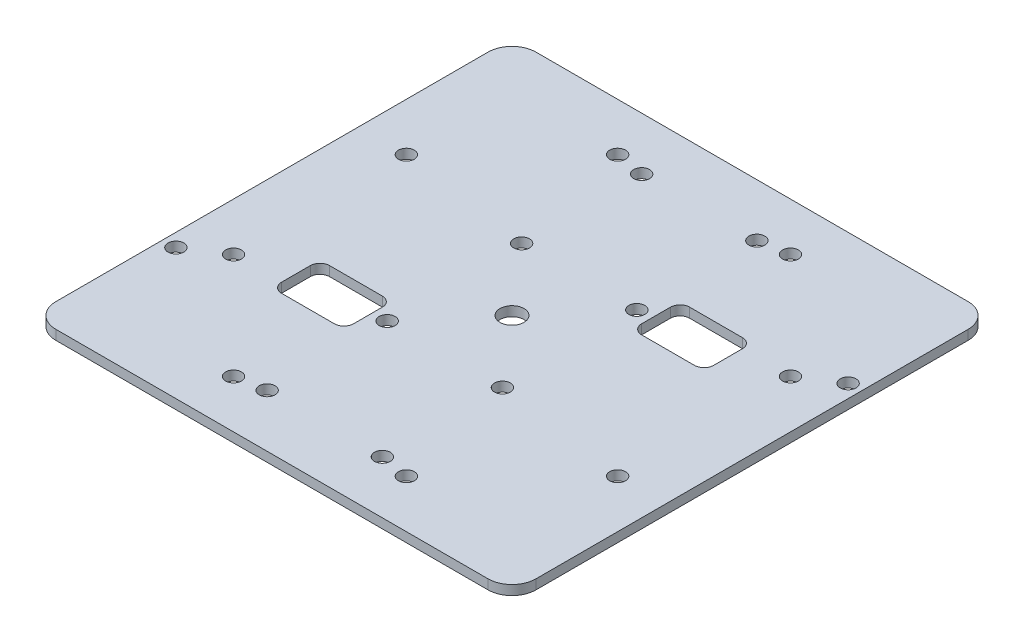
SolidWorks part; units mm, degrees
ref_plane "前视基准面" through (0, 0, 0) normal (0, 0, 1) x (1, 0, 0)
ref_plane "上视基准面" through (0, 0, 0) normal (0, 1, 0) x (1, 0, 0)
ref_plane "右视基准面" through (0, 0, 0) normal (1, 0, 0) x (0, 0, -1)
sketch "草图1" plane through (0, 0, 0) normal (0, 1, 0) x (1, 0, 0)
  line L1 (-50, -50) -> (50, -50)
  line L2 (-50, -50) -> (-50, 50)
  line L3 (-50, 50) -> (50, 50)
  line L4 (50, -50) -> (50, 50)
  line L5 (-50, -50) -> (50, 50) construction
  line L6 (-50, 50) -> (50, -50) construction
  point P0 (0, 0)
  dimension "D1" = 100
  dimension "D2" = 100
extrude "凸台-拉伸1" add sketch "草图1" along normal blind 2
sketch "草图2" plane through (0, 2, 0) normal (0, 1, 0) x (1, 0, 0)
  circle A0 centre (0, 0) radius 2.5
  dimension "D1" = 5
extrude "临时配合孔" cut sketch "草图2" against normal up to next
sketch "草图3" plane through (0, 2, 0) normal (0, 1, 0) x (1, 0, 0)
  line L1 (-12, 39) -> (12, 39) construction
  line L2 (-12, 39) -> (-12, -39) construction
  line L3 (-12, -39) -> (12, -39) construction
  line L4 (12, 39) -> (12, -39) construction
  line L5 (-12, 39) -> (12, -39) construction
  line L6 (-12, -39) -> (12, 39) construction
  circle A0 centre (-12, 39) radius 1.65
  circle A1 centre (12, 39) radius 1.65
  point P0 (0, 0)
  dimension "D3" = 3.3
  dimension "D1" = 24
  dimension "D2" = 78
extrude "切除-拉伸2" cut sketch "草图3" against normal up to next
pattern_linear "阵列(线性)1" count 2 spacing 25 along (0, 0, 1) of "切除-拉伸2"
mirror "镜向1" about plane through (0, 0, 0) normal (0, 0, 1) of "阵列(线性)1", "切除-拉伸2"
sketch "草图4" plane through (0, 0, 0) normal (1, 0, 0) x (0, 0, -1)
  line L0 (0, 0) -> (0, 2) construction
  line L1 (-50, 2) -> (50, 2) construction
sketch "草图5" plane through (0, 2, 0) normal (0, 1, 0) x (1, 0, 0)
  line L0 (50, 50) -> (-50, 50) construction
  line L1 (50, -50) -> (50, 50) construction
  circle A0 centre (47.25, 22.75) radius 1.65
  dimension "D2" = 3.3
  dimension "D1" = 27.25
  dimension "D3" = 2.75
extrude "切除-拉伸3" cut sketch "草图5" against normal up to next
pattern_circular "阵列(圆周)1" count 2 over 360 about axis through (0, 0, 0) along (0, 1, 0) of "切除-拉伸3"
sketch "草图6" plane through (0, 2, 0) normal (0, 1, 0) x (1, 0, 0)
  line L1 (-40, -18) -> (40, -18) construction
  line L2 (-40, -18) -> (-40, 18) construction
  line L3 (-40, 18) -> (40, 18) construction
  line L4 (40, -18) -> (40, 18) construction
  line L5 (-40, -18) -> (40, 18) construction
  line L6 (-40, 18) -> (40, -18) construction
  circle A0 centre (-40, 18) radius 1.65
  circle A1 centre (-40, -18) radius 1.65
  circle A2 centre (40, -18) radius 1.65
  circle A3 centre (40, 18) radius 1.65
  point P0 (0, 0)
  dimension "D3" = 3.3
  dimension "D1" = 36
  dimension "D2" = 80
extrude "切除-拉伸4" cut sketch "草图6" against normal up to next
pattern_circular "阵列(圆周)2" count 2 over 90 about axis through (0, 0, 0) along (0, 1, 0) of "切除-拉伸4"
sketch "草图7" plane through (0, 2, 0) normal (0, 1, 0) x (1, 0, 0)
  line L1 (-15, -10) -> (15, -10) construction
  line L2 (-15, -10) -> (-15, 10) construction
  line L3 (-15, 10) -> (15, 10) construction
  line L4 (15, -10) -> (15, 10) construction
  line L5 (-15, -10) -> (15, 10) construction
  line L6 (-15, 10) -> (15, -10) construction
  line L7 (-15, -10) -> (-30, -10)
  line L8 (-15, -10) -> (-15, -20)
  line L9 (-15, -20) -> (-30, -20)
  line L10 (-30, -10) -> (-30, -20)
  line L11 (15, 10) -> (30, 10)
  line L12 (15, 10) -> (15, 20)
  line L13 (15, 20) -> (30, 20)
  line L14 (30, 10) -> (30, 20)
  point P0 (0, 0)
  dimension "D1" = 30
  dimension "D2" = 20
  dimension "D3" = 15
  dimension "D4" = 10
extrude "切除-拉伸5" cut sketch "草图7" against normal up to next
fillet "圆角1" radius 2 8 edges at (30, 1, -20) (30, 1, -10) (15, 1, -10) (15, 1, -20) (-15, 1, 10) (-15, 1, 20) (-30, 1, 20) (-30, 1, 10)
fillet "圆角2" radius 5 4 edges at (50, 1, -50) (50, 1, 50) (-50, 1, 50) (-50, 1, -50)
